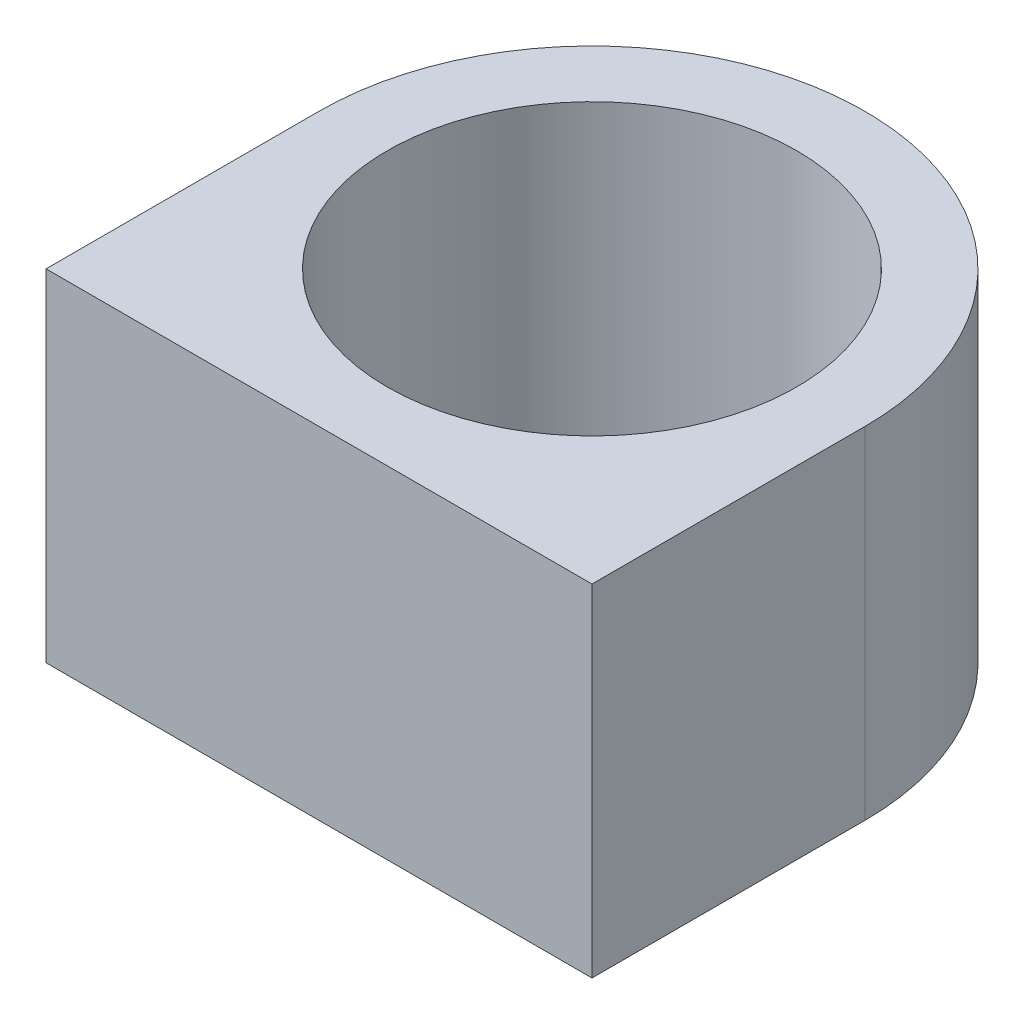
SolidWorks part; units mm, degrees
ref_plane "Front Plane" through (0, 0, 0) normal (0, 0, 1) x (1, 0, 0)
ref_plane "Top Plane" through (0, 0, 0) normal (0, 1, 0) x (1, 0, 0)
ref_plane "Right Plane" through (0, 0, 0) normal (1, 0, 0) x (0, 0, -1)
sketch "Sketch1" plane through (0, 0, 0) normal (0, 1, 0) x (1, 0, 0)
  line L0 (4, 0) -> (4, -4)
  line L1 (4, -4) -> (-4, -4)
  line L2 (-4, -4) -> (-4, 0)
  circle A0 centre (0, 0) radius 3
  arc A1 (4, 0) -> (-4, 0) centre (0, 0) ccw
  dimension "D1" = 6
  dimension "D2" = 8
extrude "Boss-Extrude1" add sketch "Sketch1" along normal blind 5
